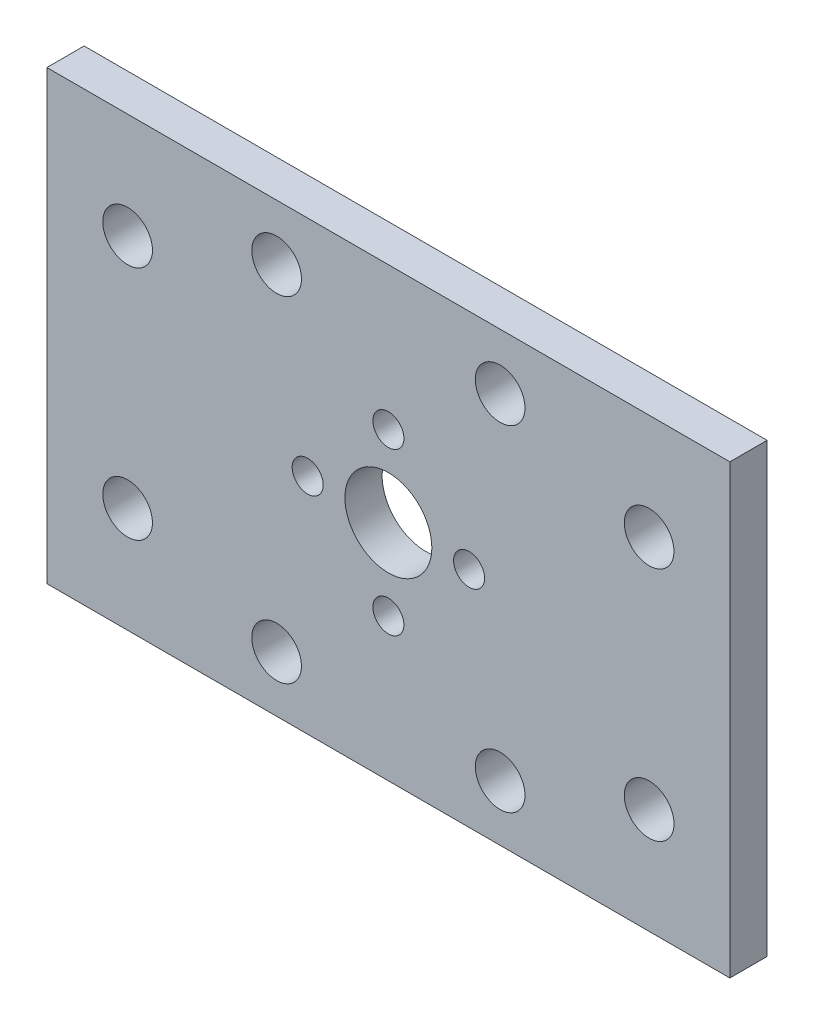
SolidWorks part; units mm, degrees
material "Alumina"
ref_plane "Front Plane" through (0, 0, 0) normal (0, 0, 1) x (1, 0, 0)
ref_plane "Top Plane" through (0, 0, 0) normal (0, 1, 0) x (1, 0, 0)
ref_plane "Right Plane" through (0, 0, 0) normal (1, 0, 0) x (0, 0, -1)
sketch "Sketch1" plane through (0, 0, 0) normal (0, 0, 1) x (1, 0, 0)
  line L8 (0, 0) -> (50000, 0) construction
  line L11 (0, 0) -> (0, -50000) construction
  line L13 (-27.5, 18) -> (27.5, 18)
  line L14 (-27.5, 18) -> (-27.5, -18)
  line L15 (-27.5, -18) -> (27.5, -18)
  line L16 (27.5, 18) -> (27.5, -18)
  line L17 (-27.5, 18) -> (27.5, -18) construction
  line L18 (-27.5, -18) -> (27.5, 18) construction
  circle A0 centre (-9, 13.5) radius 2
  circle A1 centre (-21, 9.5) radius 2
  circle A14 centre (-9, -13.5) radius 2
  circle A15 centre (-21, -9.5) radius 2
  circle A18 centre (9, -13.5) radius 2
  circle A19 centre (21, -9.5) radius 2
  circle A20 centre (9, 13.5) radius 2
  circle A21 centre (21, 9.5) radius 2
  circle A22 centre (0, 0) radius 3.5
  circle A23 centre (0, 0) radius 6.5 construction
  circle A24 centre (0, 6.5) radius 1.25
  circle A25 centre (6.5, 0) radius 1.25
  circle A26 centre (0, -6.5) radius 1.25
  circle A27 centre (-6.5, 0) radius 1.25
  point P4 (0, 0)
  point P29 (0, 0)
  dimension "D1" = 4
  dimension "D2" = 7
  dimension "D3" = 13
  dimension "D4" = 2.5
  dimension "D5" = 4
  dimension "D6" = 55
  dimension "D7" = 36
  dimension "D8" = 9.5
  dimension "D9" = 13.5
  dimension "D10" = 9
  dimension "D11" = 21
extrude "Boss-Extrude1" add sketch "Sketch1" along normal mid plane 3
